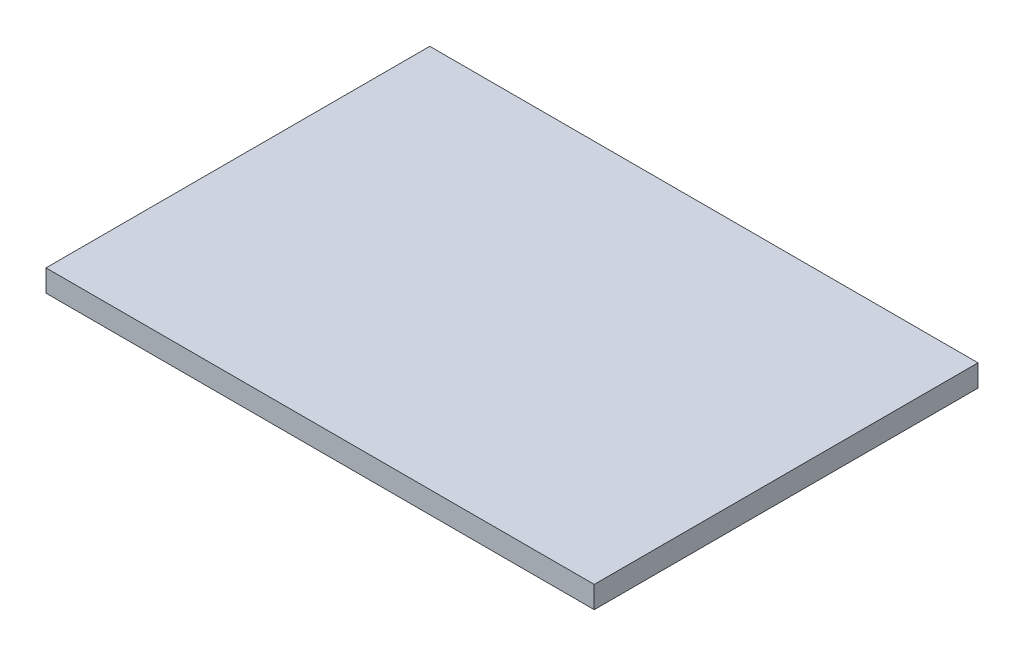
SolidWorks part; units mm, degrees
material "Cast Alloy Steel"
ref_plane "Front Plane" through (0, 0, 0) normal (0, 0, 1) x (1, 0, 0)
ref_plane "Top Plane" through (0, 0, 0) normal (0, 1, 0) x (1, 0, 0)
ref_plane "Right Plane" through (0, 0, 0) normal (1, 0, 0) x (0, 0, -1)
sketch "Sketch1" plane through (0, 0, 0) normal (0, 1, 0) x (1, 0, 0)
  line L1 (-13.97, 13.97) -> (13.97, 13.97)
  line L2 (-13.97, 13.97) -> (-13.97, -13.97)
  line L3 (-13.97, -13.97) -> (13.97, -13.97)
  line L4 (13.97, 13.97) -> (13.97, -13.97)
  line L5 (-13.97, 13.97) -> (13.97, -13.97) construction
  line L6 (-13.97, -13.97) -> (13.97, 13.97) construction
  point P0 (0, 0)
  dimension "D1" = 27.94
  dimension "D2" = 27.94
extrude "Boss-Extrude1" add sketch "Sketch1" along normal blind 127
sketch "Sketch2" plane through (0, 127, 0) normal (0, 1, 0) x (1, 0, 0)
  line L8 (11.43, -11.43) -> (11.43, 11.43)
  line L9 (11.43, 11.43) -> (-11.43, 11.43)
  line L10 (-11.43, 11.43) -> (-11.43, -11.43)
  line L11 (-11.43, -11.43) -> (11.43, -11.43)
  line L12 (11.43, -11.43) -> (11.43, 11.43)
  line L13 (11.43, 11.43) -> (-11.43, 11.43)
  line L14 (-11.43, 11.43) -> (-11.43, -11.43)
  line L15 (-11.43, -11.43) -> (11.43, -11.43)
  dimension "D1" = 2.54
extrude "Cut-Extrude1" cut sketch "Sketch2" against normal up to next
sketch "Sketch3" plane through (0, 127, 0) normal (0, 1, 0) x (1, 0, 0)
  line L1 (13.97, 13.97) -> (-36.83, 13.97)
  line L2 (13.97, 13.97) -> (13.97, -163.83)
  line L3 (13.97, -163.83) -> (-36.83, -163.83)
  line L4 (-36.83, 13.97) -> (-36.83, -163.83)
  dimension "D1" = 177.8
  dimension "D2" = 50.8
extrude "Boss-Extrude2" add sketch "Sketch3" along normal blind 10.16
sketch "Sketch4" plane through (13.97, 0, 0) normal (1, 0, 0) x (0, 0, -1)
  line L0 (-13.97, 0) -> (13.97, 0) construction
  line L1 (13.97, 137.16) -> (13.97, 0) construction
  circle A0 centre (0, 25.4) radius 6.35
  circle A1 centre (0, 43.18) radius 6.35
  circle A2 centre (0, 60.96) radius 6.35
  circle A3 centre (0, 78.74) radius 6.35
  circle A4 centre (0, 96.52) radius 6.35
  dimension "D1" = 12.7
  dimension "D2" = 25.4
  dimension "D3" = 13.97
  dimension "D5" = 43.18
  dimension "D4" = 5
extrude "Cut-Extrude2" cut sketch "Sketch4" against normal up to next
sketch "Sketch5" plane through (13.97, 0, 0) normal (1, 0, 0) x (0, 0, -1)
  line L1 (-163.83, 137.16) -> (13.97, 137.16)
  line L2 (-163.83, 137.16) -> (-163.83, 127)
  line L3 (-163.83, 127) -> (13.97, 127)
  line L4 (13.97, 137.16) -> (13.97, 127)
extrude "Boss-Extrude3" add sketch "Sketch5" along normal blind 203.2
ref_plane "Plane1" through (90.17, 0, 0) normal (-1, 0, 0) x (0, 0, 1)
sketch "Sketch6" plane through (0, 127, 0) normal (0, -1, 0) x (1, 0, 0)
  line L8 (-36.83, -13.97) -> (-13.97, -13.97)
  line L9 (-13.97, -13.97) -> (-13.97, 13.97)
  line L10 (-13.97, 13.97) -> (13.97, 13.97)
  line L11 (13.97, 13.97) -> (13.97, -13.97)
  line L12 (13.97, -13.97) -> (217.17, -13.97)
  line L13 (217.17, -13.97) -> (217.17, 163.83)
  line L14 (217.17, 163.83) -> (-36.83, 163.83)
  line L15 (-36.83, 163.83) -> (-36.83, -13.97)
  line L16 (-36.83, -13.97) -> (-13.97, -13.97)
  line L17 (-13.97, -13.97) -> (-13.97, 13.97)
  line L18 (-13.97, 13.97) -> (13.97, 13.97)
  line L19 (13.97, 13.97) -> (13.97, -13.97)
  line L20 (13.97, -13.97) -> (217.17, -13.97)
  line L21 (217.17, -13.97) -> (217.17, 163.83)
  line L22 (217.17, 163.83) -> (-36.83, 163.83)
  line L23 (-36.83, 163.83) -> (-36.83, -13.97)
  circle A0 centre (90.17, 43.5017) radius 7.5
  dimension "D1" = 0
sketch "Sketch7" plane through (0, 127, 0) normal (0, -1, 0) x (1, 0, 0)
  circle A0 centre (90.17, 43.5017) radius 7.5
extrude "Cut-Extrude4" cut sketch "Sketch7" against normal blind 5.08
